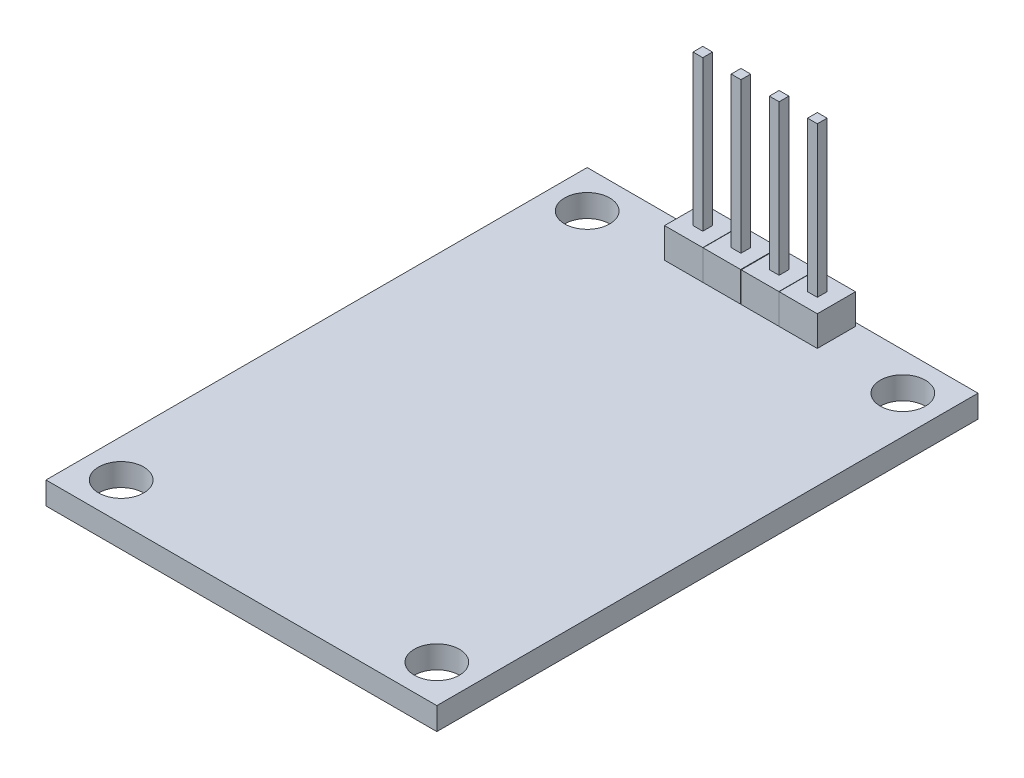
SolidWorks part; units mm, degrees
ref_plane "Ön Düzlem" through (0, 0, 0) normal (0, 0, 1) x (1, 0, 0)
ref_plane "Üst Düzlem" through (0, 0, 0) normal (0, 1, 0) x (1, 0, 0)
ref_plane "Sağ Düzlem" through (0, 0, 0) normal (1, 0, 0) x (0, 0, -1)
sketch "Sketch1" plane through (0, 0, 0) normal (0, 1, 0) x (1, 0, 0)
  line L1 (-13, 18) -> (13, 18)
  line L2 (-13, 18) -> (-13, -18)
  line L3 (-13, -18) -> (13, -18)
  line L4 (13, 18) -> (13, -18)
  line L5 (-13, 18) -> (13, -18) construction
  line L6 (-13, -18) -> (13, 18) construction
  point P0 (0, 0)
  dimension "D1" = 26
  dimension "D2" = 36
extrude "Boss-Extrude1" add sketch "Sketch1" along normal blind 1.5
sketch "Sketch2" plane through (0, 1.5, 0) normal (0, 1, 0) x (1, 0, 0)
  line L1 (-10.5, 15.5) -> (10.5, 15.5) construction
  line L2 (-10.5, 15.5) -> (-10.5, -15.5) construction
  line L3 (-10.5, -15.5) -> (10.5, -15.5) construction
  line L4 (10.5, 15.5) -> (10.5, -15.5) construction
  line L5 (-10.5, 15.5) -> (10.5, -15.5) construction
  line L6 (-10.5, -15.5) -> (10.5, 15.5) construction
  circle A0 centre (-10.5, 15.5) radius 1.5
  circle A1 centre (10.5, 15.5) radius 1.5
  circle A2 centre (10.5, -15.5) radius 1.5
  circle A3 centre (-10.5, -15.5) radius 1.5
  point P0 (0, 0)
  dimension "D3" = 3
  dimension "D4" = 3
  dimension "D5" = 3
  dimension "D6" = 3
  dimension "D1" = 31
  dimension "D2" = 21
extrude "Cut-Extrude1" cut sketch "Sketch2" against normal blind 1.5
sketch "Sketch3" plane through (0, 1.5, 0) normal (0, 1, 0) x (1, 0, 0)
  line L0 (-13, 16.5) -> (13, 16.5) construction
  line L1 (-13, 18) -> (-13, -18) construction
  line L2 (13, -18) -> (13, 18) construction
  line L3 (13, 18) -> (-13, 18) construction
  line L4 (0.02, 17.77) -> (2.52, 17.77)
  line L5 (0.02, 17.77) -> (0.02, 15.23)
  line L6 (0.02, 15.23) -> (2.52, 15.23)
  line L7 (2.52, 17.77) -> (2.52, 15.23)
  line L8 (0.02, 17.77) -> (2.52, 15.23) construction
  line L9 (0.02, 15.23) -> (2.52, 17.77) construction
  line L10 (0, 16.5) -> (0, 9.996) construction
  line L11 (-2.54, 15.23) -> (-5.08, 15.23)
  line L12 (2.54, 17.77) -> (5.08, 17.77)
  line L13 (2.54, 17.77) -> (2.54, 15.23)
  line L14 (2.54, 15.23) -> (5.08, 15.23)
  line L15 (5.08, 17.77) -> (5.08, 15.23)
  line L16 (2.54, 17.77) -> (5.08, 15.23) construction
  line L17 (2.54, 15.23) -> (5.08, 17.77) construction
  line L18 (-5.08, 17.77) -> (-5.08, 15.23)
  line L19 (-2.54, 17.77) -> (-5.08, 17.77)
  line L20 (-2.54, 17.77) -> (-2.54, 15.23)
  line L21 (-0.02, 15.23) -> (-2.52, 15.23)
  line L22 (-2.52, 17.77) -> (-2.52, 15.23)
  line L23 (-0.02, 17.77) -> (-2.52, 17.77)
  line L24 (-0.02, 17.77) -> (-0.02, 15.23)
  point P6 (1.27, 16.5)
  point P17 (3.81, 16.5)
  dimension "D1" = 2.5
  dimension "D2" = 2.54
  dimension "D3" = 1.5
  dimension "D4" = 1.27
  dimension "D5" = 2.54
  dimension "D6" = 2.54
  dimension "D7" = 2.54
extrude "Boss-Extrude2" add sketch "Sketch3" along normal blind 2
sketch "Sketch4" plane through (0, 3.5, 0) normal (0, 1, 0) x (1, 0, 0)
  line L0 (-5.08, 16.5) -> (-2.54, 16.5) construction
  line L1 (-5.08, 17.77) -> (-5.08, 15.23) construction
  line L2 (-2.54, 15.23) -> (-2.54, 17.77) construction
  line L3 (-2.54, 16.5) -> (-2.52, 16.5) construction
  line L4 (-2.52, 17.77) -> (-2.52, 15.23) construction
  line L5 (-2.52, 16.5) -> (-0.02, 16.5) construction
  line L6 (-0.02, 15.23) -> (-0.02, 17.77) construction
  line L7 (-0.02, 16.5) -> (0.02, 16.5) construction
  line L8 (0.02, 17.77) -> (0.02, 15.23) construction
  line L9 (0.02, 16.5) -> (2.52, 16.5) construction
  line L10 (2.52, 15.23) -> (2.52, 17.77) construction
  line L11 (2.52, 16.5) -> (2.54, 16.5) construction
  line L12 (2.54, 17.77) -> (2.54, 15.23) construction
  line L13 (2.54, 16.5) -> (5.08, 16.5) construction
  line L14 (5.08, 15.23) -> (5.08, 17.77) construction
  line L16 (-4.135, 16.825) -> (-3.485, 16.825)
  line L17 (-4.135, 16.825) -> (-4.135, 16.175)
  line L18 (-4.135, 16.175) -> (-3.485, 16.175)
  line L19 (-3.485, 16.825) -> (-3.485, 16.175)
  line L20 (-4.135, 16.825) -> (-3.485, 16.175) construction
  line L21 (-4.135, 16.175) -> (-3.485, 16.825) construction
  line L22 (-1.595, 16.825) -> (-0.945, 16.825)
  line L23 (-1.595, 16.825) -> (-1.595, 16.175)
  line L24 (-1.595, 16.175) -> (-0.945, 16.175)
  line L25 (-0.945, 16.825) -> (-0.945, 16.175)
  line L26 (-1.595, 16.825) -> (-0.945, 16.175) construction
  line L27 (-1.595, 16.175) -> (-0.945, 16.825) construction
  line L28 (0.945, 16.825) -> (1.595, 16.825)
  line L29 (0.945, 16.825) -> (0.945, 16.175)
  line L30 (0.945, 16.175) -> (1.595, 16.175)
  line L31 (1.595, 16.825) -> (1.595, 16.175)
  line L32 (0.945, 16.825) -> (1.595, 16.175) construction
  line L33 (0.945, 16.175) -> (1.595, 16.825) construction
  line L34 (3.485, 16.825) -> (4.135, 16.825)
  line L35 (3.485, 16.825) -> (3.485, 16.175)
  line L36 (3.485, 16.175) -> (4.135, 16.175)
  line L37 (4.135, 16.825) -> (4.135, 16.175)
  line L38 (3.485, 16.825) -> (4.135, 16.175) construction
  line L39 (3.485, 16.175) -> (4.135, 16.825) construction
  point P6 (-3.81, 16.5)
  point P29 (-1.27, 16.5)
  point P34 (1.27, 16.5)
  point P39 (3.81, 16.5)
  dimension "D1" = 0.65
  dimension "D2" = 0.65
  dimension "D3" = 0.65
  dimension "D4" = 0.65
  dimension "D5" = 0.65
  dimension "D6" = 0.65
  dimension "D7" = 0.65
  dimension "D8" = 0.65
extrude "Boss-Extrude3" add sketch "Sketch4" along normal blind 10 and the other way blind 5
sketch "Sketch5" plane through (0, 0, 0) normal (0, -1, 0) x (1, 0, 0)
  line L0 (-13, 18) -> (13, 18) construction
  line L1 (-7.5, 6.5) -> (7.5, 6.5)
  line L2 (-7.5, 6.5) -> (-7.5, -5)
  line L3 (-7.5, -5) -> (7.5, -5)
  line L4 (7.5, 6.5) -> (7.5, -5)
  line L5 (-7.5, 6.5) -> (7.5, -5) construction
  line L6 (-7.5, -5) -> (7.5, 6.5) construction
  point P0 (0, 0.75)
  dimension "D1" = 15
  dimension "D2" = 11.5
  dimension "D3" = 11.5
extrude "Boss-Extrude4" add sketch "Sketch5" along normal blind 2.5
sketch "Sketch6" plane through (0, 0, 0) normal (0, -1, 0) x (1, 0, 0)
  line L1 (0.162, -10.3844) -> (1.9956, -10.3844)
  line L2 (0.162, -10.3844) -> (0.162, -11.6747)
  line L3 (0.162, -11.6747) -> (1.9956, -11.6747)
  line L4 (1.9956, -10.3844) -> (1.9956, -11.6747)
  line L5 (0.162, -10.3844) -> (1.9956, -11.6747) construction
  line L6 (0.162, -11.6747) -> (1.9956, -10.3844) construction
  line L7 (2.4709, -10.3844) -> (4.4403, -10.3844)
  line L8 (2.4709, -10.3844) -> (2.4709, -11.6747)
  line L9 (2.4709, -11.6747) -> (4.4403, -11.6747)
  line L10 (4.4403, -10.3844) -> (4.4403, -11.6747)
  line L11 (2.4709, -10.3844) -> (4.4403, -11.6747) construction
  line L12 (2.4709, -11.6747) -> (4.4403, -10.3844) construction
  line L13 (4.9836, -10.3844) -> (6.6813, -10.3844)
  line L14 (4.9836, -10.3844) -> (4.9836, -11.6747)
  line L15 (4.9836, -11.6747) -> (6.6813, -11.6747)
  line L16 (6.6813, -10.3844) -> (6.6813, -11.6747)
  line L17 (4.9836, -10.3844) -> (6.6813, -11.6747) construction
  line L18 (4.9836, -11.6747) -> (6.6813, -10.3844) construction
  line L19 (7.2585, -10.3844) -> (8.8205, -10.3844)
  line L20 (7.2585, -10.3844) -> (7.2585, -11.6747)
  line L21 (7.2585, -11.6747) -> (8.8205, -11.6747)
  line L22 (8.8205, -10.3844) -> (8.8205, -11.6747)
  line L23 (7.2585, -10.3844) -> (8.8205, -11.6747) construction
  line L24 (7.2585, -11.6747) -> (8.8205, -10.3844) construction
  point P0 (1.0788, -11.0295)
  point P5 (3.4556, -11.0295)
  point P10 (5.8324, -11.0295)
  point P15 (8.0395, -11.0295)
extrude "Boss-Extrude5" add sketch "Sketch6" along normal blind 1.5
fillet "Fillet1" radius 0.5 4 edges at (0, -2.5, -5) (-7.5, -2.5, 0.75) (0, -2.5, 6.5) (7.5, -2.5, 0.75)
sketch "Sketch7" plane through (0, -2.5, 0) normal (0, -1, 0) x (1, 0, 0)
  line L0 (-4.6766, -1.8606) -> (5.1292, -1.8606) construction
  text T0 "GPS"
extrude "Cut-Extrude2" cut sketch "Sketch7" against normal blind 0.5
scale "Ölçek1" scale about centroid uniform scaling yes scale factor 0.5
